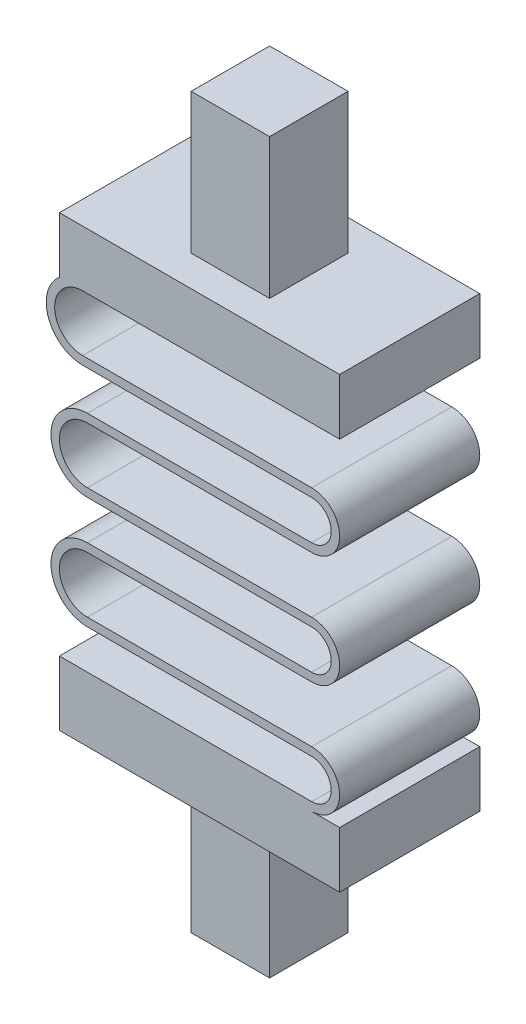
SolidWorks part; units mm, degrees
ref_plane "Front Plane" through (0, 0, 0) normal (0, 0, 1) x (1, 0, 0)
ref_plane "Top Plane" through (0, 0, 0) normal (0, 1, 0) x (1, 0, 0)
ref_plane "Right Plane" through (0, 0, 0) normal (1, 0, 0) x (0, 0, -1)
sketch "Sketch2" plane through (0, 0, 0) normal (0, 0, 1) x (1, 0, 0)
  line L0 (-4.1693, 2.5732) -> (4, 2.5732)
  line L1 (-5, -7.4268) -> (5, -7.4268)
  line L2 (-5, -7.4268) -> (-5, -9.4268)
  line L3 (-5, -9.4268) -> (5, -9.4268)
  line L4 (5, -7.4268) -> (5, -9.4268)
  line L5 (-5, 6.5732) -> (5, 6.5732)
  line L6 (-5, 6.5732) -> (-5, 4.5732)
  line L7 (-5, 4.5732) -> (5, 4.5732)
  line L8 (5, 6.5732) -> (5, 4.5732)
  line L10 (-4, 0.5732) -> (4, 0.5732)
  line L12 (-4, -1.4268) -> (4, -1.4268)
  line L14 (-4, -3.4268) -> (4, -3.4268)
  line L16 (-4, 0.5732) -> (4, 0.5732)
  line L18 (-4, -1.4268) -> (4, -1.4268)
  line L20 (-4, -5.4268) -> (4, -5.4268)
  line L22 (-5, -7.4268) -> (5, -7.4268)
  line L24 (-4, -3.4268) -> (4, -3.4268)
  line L26 (-4, -5.4268) -> (4, -5.4268)
  line L28 (-5, 4.5732) -> (5, 4.5732)
  line L30 (-4.1693, 2.5732) -> (4, 2.5732)
  line L31 (-4.1693, 2.2732) -> (4, 2.2732)
  line L32 (-4, 0.8732) -> (4, 0.8732)
  line L33 (-4, -1.7268) -> (4, -1.7268)
  line L34 (-4, -3.1268) -> (4, -3.1268)
  line L35 (-4, -5.7268) -> (4, -5.7268)
  line L36 (4, -7.1268) -> (-5, -7.1268)
  line L37 (-5, -7.1268) -> (-5, -7.4268)
  arc A0 (-4.1693, 4.5732) -> (-4.1693, 2.5732) centre (-4.1693, 3.5732) ccw
  arc A1 (4, 0.5732) -> (4, 2.5732) centre (4, 1.5732) ccw
  arc A3 (-4, 0.5732) -> (-4, -1.4268) centre (-4, -0.4268) ccw
  arc A4 (4, -7.4268) -> (4, -5.4268) centre (4, -6.4268) ccw
  arc A5 (-4, -3.4268) -> (-4, -5.4268) centre (-4, -4.4268) ccw
  arc A6 (4, -3.4268) -> (4, -1.4268) centre (4, -2.4268) ccw
  arc A7 (-5, 4.5732) -> (-4.1693, 2.2732) centre (-4.1693, 3.5732) ccw
  arc A8 (4, 0.8732) -> (4, 2.2732) centre (4, 1.5732) ccw
  arc A9 (-4, 0.8732) -> (-4, -1.7268) centre (-4, -0.4268) ccw
  arc A10 (4, -3.1268) -> (4, -1.7268) centre (4, -2.4268) ccw
  arc A11 (-4, -3.1268) -> (-4, -5.7268) centre (-4, -4.4268) ccw
  arc A12 (4, -7.1268) -> (4, -5.7268) centre (4, -6.4268) ccw
  arc A13 (-4.1693, 4.8732) -> (-4.1693, 2.2732) centre (-4.1693, 3.5732) ccw construction
  point P8 (0, -7.4268)
  point P10 (0, 4.5732)
  point P53 (-5, 4.5506)
  dimension "D4" = 0.3
  dimension "D3" = 2
  dimension "D1" = 10
  dimension "D2" = 2
extrude "Boss-Extrude1" add sketch "Sketch2" along normal blind 5 contours L8 L5 L6 L7 L28 | A12 L36 L37 L1 A4 L20 A5 L14 A6 L12 A3 L10 A1 L0 A0 L7 L6 A7 L31 A8 L32 A9 L33 A10 L34 A11 L35 | L4 L22 L1 L2 L3
sketch "Sketch3" plane through (0, 6.5732, 0) normal (0, 1, 0) x (1, 0, 0)
  line L0 (0, 0) -> (0, -5) construction
  line L1 (-1.4, -3.9) -> (1.4, -3.9)
  line L2 (-1.4, -3.9) -> (-1.4, -1.1)
  line L3 (-1.4, -1.1) -> (1.4, -1.1)
  line L4 (1.4, -3.9) -> (1.4, -1.1)
  line L5 (-1.4, -3.9) -> (1.4, -1.1) construction
  line L6 (-1.4, -1.1) -> (1.4, -3.9) construction
  line L7 (-5, 0) -> (5, 0) construction
  line L8 (-5, -5) -> (5, -5) construction
  point P0 (0, -2.5)
  point P11 (0, 0)
  point P12 (0, -2.5)
  dimension "D1" = 2.8
  dimension "D2" = 2.8
extrude "Boss-Extrude2" add sketch "Sketch3" along normal blind 5
sketch "Sketch4" plane through (0, -9.4268, 0) normal (0, -1, 0) x (1, 0, 0)
  line L0 (0, 5) -> (0, 0) construction
  line L1 (-5, 5) -> (5, 5) construction
  line L3 (1.4, 1.1) -> (-1.4, 1.1)
  line L4 (1.4, 1.1) -> (1.4, 3.9)
  line L5 (1.4, 3.9) -> (-1.4, 3.9)
  line L6 (-1.4, 1.1) -> (-1.4, 3.9)
  line L7 (1.4, 1.1) -> (-1.4, 3.9) construction
  line L8 (1.4, 3.9) -> (-1.4, 1.1) construction
  point P5 (0, 2.5)
  dimension "D1" = 2.8
  dimension "D2" = 2.8
extrude "Boss-Extrude3" add sketch "Sketch4" along normal blind 5
